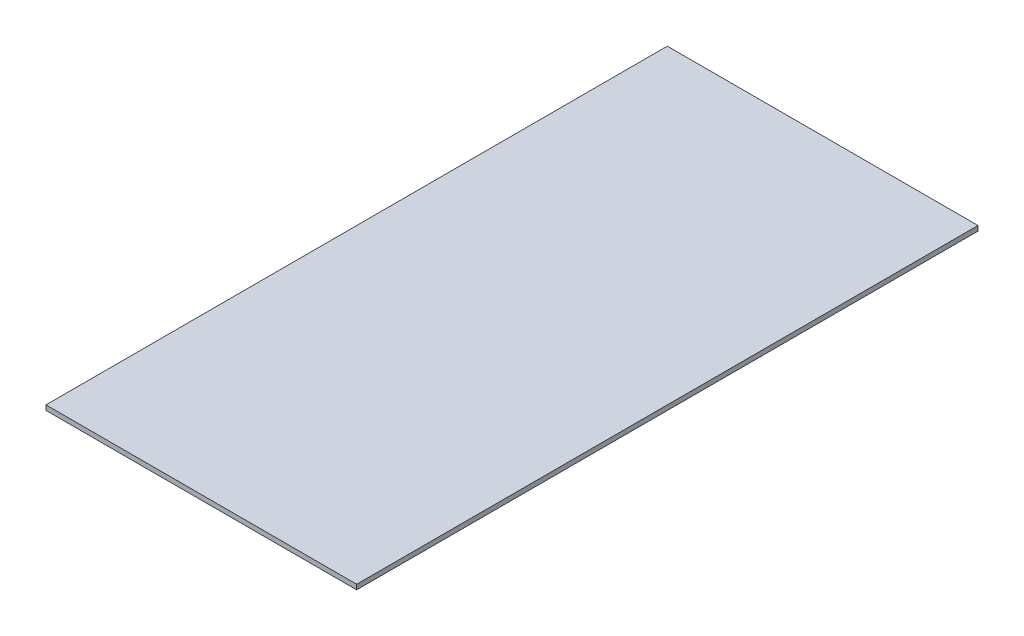
SolidWorks part; units mm, degrees
material "Pine"
ref_plane "Front" through (0, 0, 0) normal (0, 0, 1) x (1, 0, 0)
ref_plane "Top" through (0, 0, 0) normal (0, 1, 0) x (1, 0, 0)
ref_plane "Right" through (0, 0, 0) normal (1, 0, 0) x (0, 0, -1)
sketch "Sketch1" plane through (0, 0, 0) normal (0, 1, 0) x (1, 0, 0)
  line L1 (-609.6, 2438.4) -> (609.6, 2438.4)
  line L2 (-609.6, 2438.4) -> (-609.6, 0)
  line L3 (-609.6, 0) -> (609.6, 0)
  line L4 (609.6, 2438.4) -> (609.6, 0)
  dimension "D1" = 1219.2
  dimension "D2" = 2438.4
extrude "Extrude1" add sketch "Sketch1" against normal blind 19.05
